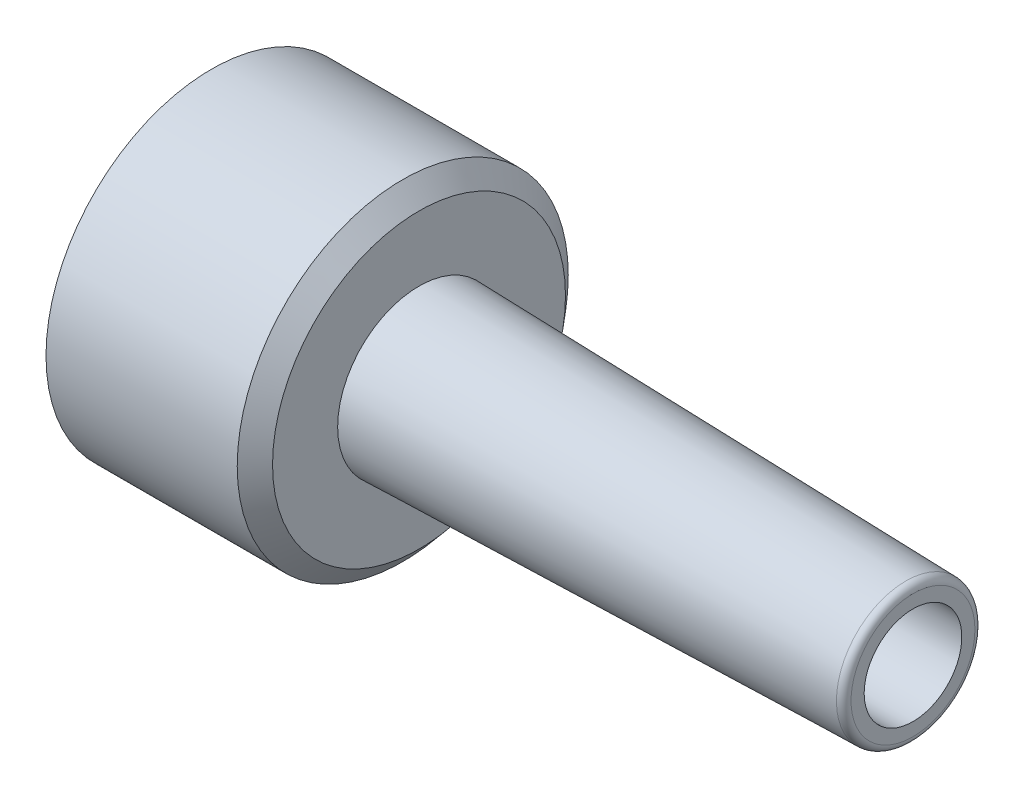
SolidWorks part; units mm, degrees
ref_plane "Front Plane" through (0, 0, 0) normal (0, 0, 1) x (1, 0, 0)
ref_plane "Top Plane" through (0, 0, 0) normal (0, 1, 0) x (1, 0, 0)
ref_plane "Right Plane" through (0, 0, 0) normal (1, 0, 0) x (0, 0, -1)
sketch "Sketch2" plane through (0, 0, 0) normal (0, 1, 0) x (1, 0, 0)
  line L0 (8.8, -32.1) -> (12.1, -44.75)
  line L1 (12.1, -44.75) -> (63.8, -44.75)
  line L2 (63.8, -44.75) -> (68.2, -39.6)
  line L3 (68.2, -39.6) -> (68.2, -22)
  line L4 (68.2, -22) -> (201.75, -18.7)
  line L5 (-55, 0) -> (55, 0) construction
  line L6 (0, 0) -> (315.0889, 0) construction
  line L7 (201.75, -18.7) -> (201.75, -13.2)
  line L8 (157.75, -13.2) -> (201.75, -13.2)
  line L9 (156.65, -12.1) -> (156.25, -12.1)
  line L10 (156.25, -12.1) -> (156.25, -13.2)
  line L11 (156.25, -13.2) -> (155.15, -13.2)
  line L12 (155.15, -12.1) -> (131.05, -12.1)
  line L13 (131.05, -12.1) -> (131.05, -12.65)
  line L14 (131.05, -12.65) -> (129.95, -12.65)
  line L16 (129.95, -12.65) -> (129.95, -10.45)
  line L17 (129.95, -10.45) -> (56.1, -10.45)
  line L18 (56.1, -10.45) -> (56.1, -26)
  line L19 (56.1, -26) -> (51.7, -26)
  line L20 (51.7, -26) -> (51.7, -31)
  line L21 (51.7, -31) -> (23.1, -31)
  line L22 (23.1, -31) -> (23.1, -32.1)
  line L23 (23.1, -32.1) -> (8.8, -32.1)
  line L24 (155.15, -13.2) -> (155.15, -12.1)
  arc A0 (156.65, -12.1) -> (157.75, -13.2) centre (158.0162, -11.8338) ccw
  dimension "D8" = 1.3919
  dimension "D1" = 14.3
  dimension "D2" = 28.6
  dimension "D3" = 4.4
  dimension "D4" = 73.85
  dimension "D5" = 1.1
  dimension "D6" = 24.1
  dimension "D7" = 1.1
  dimension "D9" = 51.7
  dimension "D10" = 16.5
  dimension "D11" = 45.1
  dimension "D12" = 22
  dimension "D13" = 17.6
  dimension "D14" = 12.1
  dimension "D15" = 10.45
  dimension "D16" = 5
  dimension "D17" = 15.55
  dimension "D18" = 13.75
  dimension "D19" = 12.65
  dimension "D20" = 1.1
  dimension "D21" = 0.4
  dimension "D22" = 18.7
  dimension "D23" = 4.4
  dimension "D24" = 13.2
  dimension "D25" = 8.8
  dimension "D26" = 1.1
  dimension "D27" = 2.2
revolve "Revolve1" add sketch "Sketch2" angle 360 about L6
fillet "Fillet1" radius 2 1 edges at (201.75, 0, 18.7)
fillet "Fillet2" radius 1 1 edges at (51.7, 0, 31)
sketch "Sketch5" plane through (0, 0, 0) normal (0, 0, 1) x (1, 0, 0)
  line L0 (55, 0) -> (-55, 0) construction
  line L1 (12.1, 44.75) -> (12.1, -44.75) construction
  circle A0 centre (15.95, 0) radius 2.2
  dimension "D2" = 4.4
  dimension "D1" = 3.85
extrude "Cut-Extrude1" cut sketch "Sketch5" against normal through all
cosmetic thread "Cosmetic Thread3" parameters "D2"=5.4
